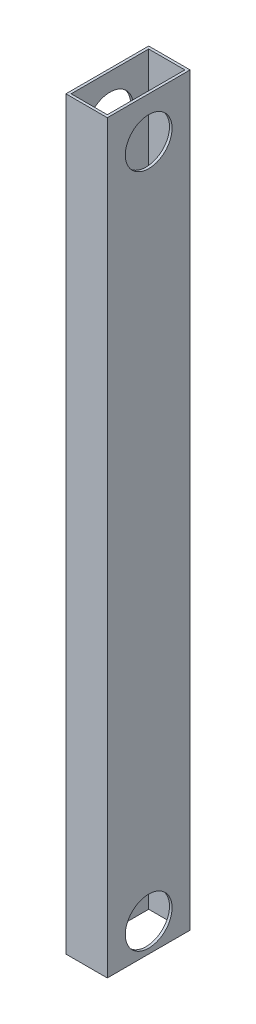
SolidWorks part; units mm, degrees
ref_plane "Front Plane" through (0, 0, 0) normal (0, 0, 1) x (1, 0, 0)
ref_plane "Top Plane" through (0, 0, 0) normal (0, 1, 0) x (1, 0, 0)
ref_plane "Right Plane" through (0, 0, 0) normal (1, 0, 0) x (0, 0, -1)
sketch "Sketch1" plane through (0, 0, 0) normal (0, 1, 0) x (1, 0, 0)
  line L1 (0, 0) -> (25.4, 0)
  line L2 (0, 0) -> (0, 50.8)
  line L3 (0, 50.8) -> (25.4, 50.8)
  line L4 (25.4, 0) -> (25.4, 50.8)
  dimension "D1" = 50.8
  dimension "D2" = 25.4
extrude "Extrude-Thin1" add sketch "Sketch1" along normal blind 457.2 thin thin type one direction reverse wall 1.5875
sketch "Sketch2" plane through (25.4, 0, 0) normal (1, 0, 0) x (0, 0, -1)
  line L0 (0, 457.2) -> (0, 0) construction
  line L1 (0, 0) -> (50.8, 0) construction
  line L2 (0, 457.2) -> (50.8, 457.2) construction
  circle A0 centre (25.4, 17.526) radius 14.351
  circle A1 centre (25.4, 431.8) radius 14.351
  point P10 (25.4, 457.2)
  dimension "D1" = 25.4
  dimension "D2" = 28.702
  dimension "D3" = 17.526
  dimension "D4" = 28.702
  dimension "D5" = 25.4
  dimension "D6" = 25.4
extrude "Cut-Extrude1" cut sketch "Sketch2" against normal through all
